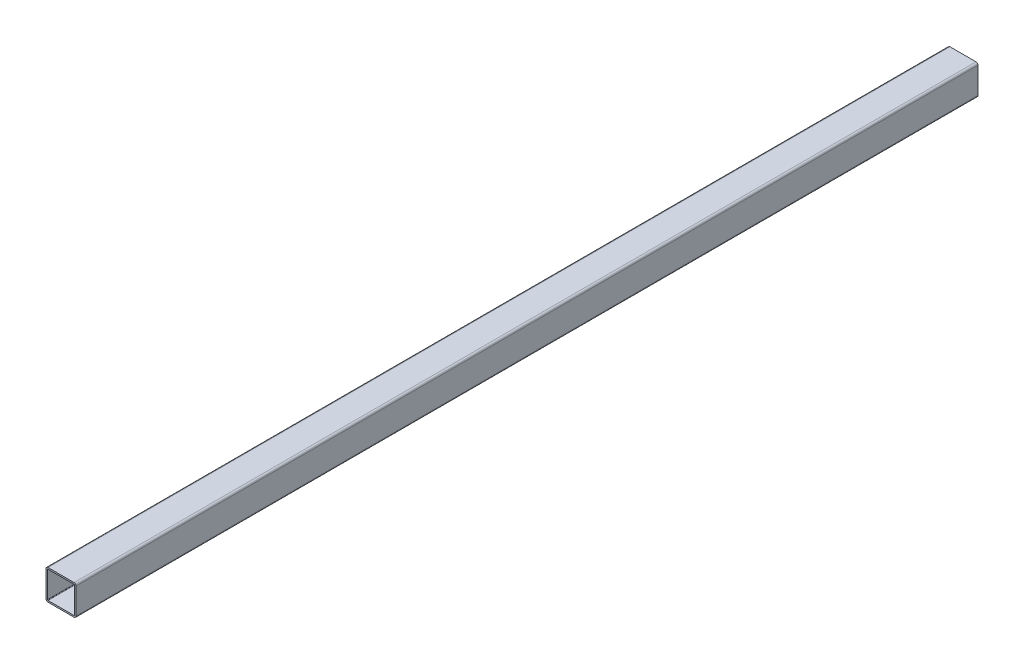
SolidWorks part; units mm, degrees
ref_plane "Спереди" through (0, 0, 0) normal (0, 0, 1) x (1, 0, 0)
ref_plane "Сверху" through (0, 0, 0) normal (0, 1, 0) x (1, 0, 0)
ref_plane "Справа" through (0, 0, 0) normal (1, 0, 0) x (0, 0, -1)
sketch "Эскиз1" plane through (0, 0, 0) normal (0, 0, 1) x (1, 0, 0)
  line L1 (2, 0) -> (28, 0)
  line L2 (0, 2) -> (0, 28)
  line L3 (2, 30) -> (28, 30)
  line L4 (30, 2) -> (30, 28)
  arc A0 (0, 2) -> (2, 0) centre (2, 2) ccw
  arc A1 (30, 2) -> (28, 0) centre (28, 2) cw
  arc A2 (28, 30) -> (30, 28) centre (28, 28) cw
  arc A3 (2, 30) -> (0, 28) centre (2, 28) ccw
  point P7 (0, 0)
  dimension "D3" = 2
  dimension "D1" = 30
  dimension "D2" = 30
extrude "Вытянуть-Тонкостенный1" add sketch "Эскиз1" along normal blind 900 thin thin type one direction reverse wall 1.5
